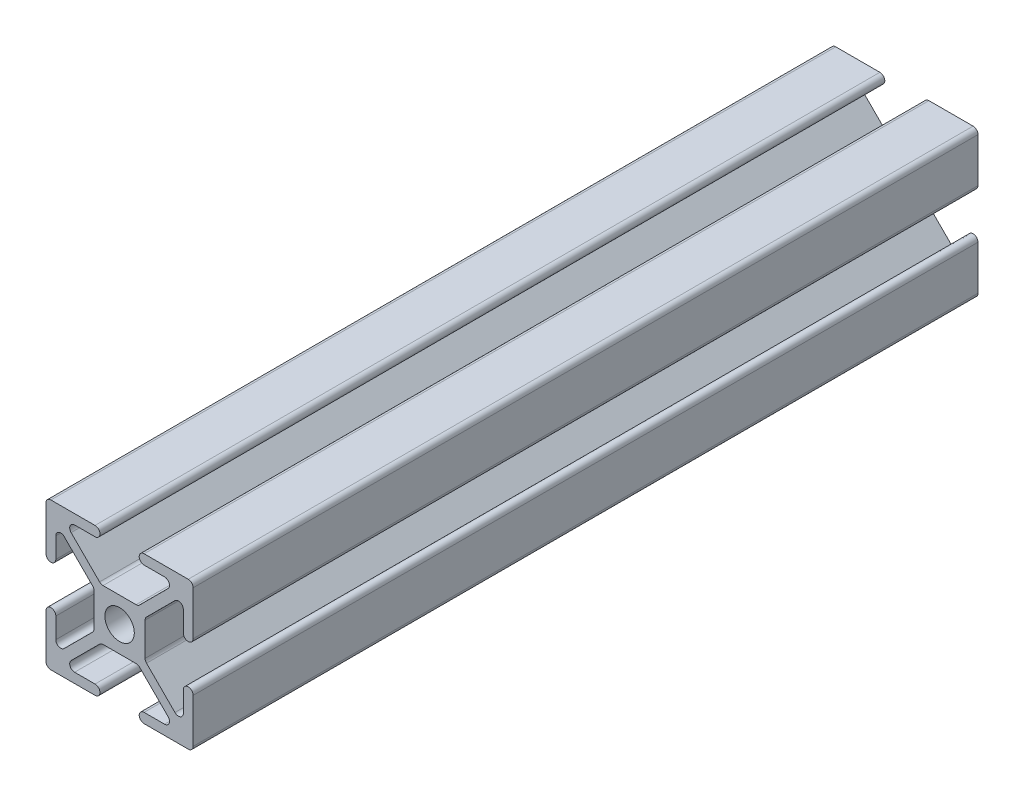
SolidWorks part; units mm, degrees
ref_plane "Alzado" through (0, 0, 0) normal (0, 0, 1) x (1, 0, 0)
ref_plane "Planta" through (0, 0, 0) normal (0, 1, 0) x (1, 0, 0)
ref_plane "Vista lateral" through (0, 0, 0) normal (1, 0, 0) x (0, 0, -1)
sketch "Croquis1" plane through (0, 0, 0) normal (0, 0, 1) x (1, 0, 0)
  line L1 (-14, 15) -> (14, 15)
  line L2 (-15, 14) -> (-15, -14)
  line L3 (-14, -15) -> (14, -15)
  line L4 (15, 14) -> (15, -14)
  line L5 (-15, 15) -> (15, -15) construction
  line L6 (-15, -15) -> (15, 15) construction
  arc A0 (-14, 15) -> (-15, 14) centre (-14, 14) ccw
  arc A1 (14, -15) -> (15, -14) centre (14, -14) ccw
  arc A2 (-14, -15) -> (-15, -14) centre (-14, -14) cw
  arc A3 (15, 14) -> (14, 15) centre (14, 14) ccw
  point P0 (0, 0)
  dimension "D3" = 1
  dimension "D4" = 1
  dimension "D1" = 30
  dimension "D2" = 30
extrude "Saliente-Extruir1" add sketch "Croquis1" against normal blind 190
sketch "Croquis2" plane through (0, 0, 0) normal (0, 0, 1) x (1, 0, 0)
  circle A0 centre (0, 0) radius 3
  dimension "D1" = 6
sketch "Croquis3" plane through (0, 0, 0) normal (0, 0, 1) x (1, 0, 0)
  line L0 (-15, 0) -> (15, 0) construction
  line L1 (4.0787, -5.4929) -> (9.8787, -11.2929)
  line L2 (-11.2929, 9.8787) -> (-5.4929, 4.0787)
  line L3 (-9.8787, 11.2929) -> (-4.0787, 5.4929)
  line L4 (-13, 9.1716) -> (-13, 5)
  line L5 (-15, 14) -> (-15, -14) construction
  line L6 (-5.2, 3.3716) -> (-5.2, -3.3716)
  line L7 (-9.1716, 13) -> (-5, 13)
  line L8 (9.8787, 11.2929) -> (4.0787, 5.4929)
  line L9 (11.2929, 9.8787) -> (5.4929, 4.0787)
  line L10 (-3.3716, 5.2) -> (3.3716, 5.2)
  line L11 (14, 15) -> (-14, 15) construction
  line L12 (13, 9.1716) -> (13, 5)
  line L13 (5.2, 3.3716) -> (5.2, -3.3716)
  line L14 (15, -14) -> (15, 14) construction
  line L15 (-9.1716, -13) -> (-5, -13)
  line L16 (-3.3716, -5.2) -> (3.3716, -5.2)
  line L17 (-14, -15) -> (14, -15) construction
  line L18 (-5.4929, -4.0787) -> (-11.2929, -9.8787)
  line L19 (5.4929, -4.0787) -> (11.2929, -9.8787)
  line L20 (-4.0787, -5.4929) -> (-9.8787, -11.2929)
  line L21 (5, -13) -> (9.1716, -13)
  line L22 (-13, -5) -> (-13, -9.1716)
  line L23 (13, -5) -> (13, -9.1716)
  line L24 (0, 15) -> (0, -5.2) construction
  line L34 (5, 13) -> (9.1716, 13)
  arc A0 (9.8787, 11.2929) -> (9.1716, 13) centre (9.1716, 12) ccw
  arc A1 (-9.8787, 11.2929) -> (-9.1716, 13) centre (-9.1716, 12) cw
  arc A2 (9.8787, 11.2929) -> (9.1716, 13) centre (9.1716, 12) ccw
  arc A3 (13, 9.1716) -> (11.2929, 9.8787) centre (12, 9.1716) ccw
  arc A4 (11.2929, -9.8787) -> (13, -9.1716) centre (12, -9.1716) ccw
  arc A5 (9.1716, -13) -> (9.8787, -11.2929) centre (9.1716, -12) ccw
  arc A6 (-9.1716, -13) -> (-9.8787, -11.2929) centre (-9.1716, -12) cw
  arc A7 (-11.2929, -9.8787) -> (-13, -9.1716) centre (-12, -9.1716) cw
  arc A8 (-13, 9.1716) -> (-11.2929, 9.8787) centre (-12, 9.1716) cw
  arc A9 (-4.0787, -5.4929) -> (-3.3716, -5.2) centre (-3.3716, -6.2) cw
  arc A10 (3.3716, -5.2) -> (4.0787, -5.4929) centre (3.3716, -6.2) cw
  arc A11 (5.4929, -4.0787) -> (5.2, -3.3716) centre (6.2, -3.3716) cw
  arc A12 (5.2, 3.3716) -> (5.4929, 4.0787) centre (6.2, 3.3716) cw
  arc A13 (3.3716, 5.2) -> (4.0787, 5.4929) centre (3.3716, 6.2) ccw
  arc A14 (-3.3716, 5.2) -> (-4.0787, 5.4929) centre (-3.3716, 6.2) cw
  arc A15 (-5.4929, -4.0787) -> (-5.2, -3.3716) centre (-6.2, -3.3716) ccw
  arc A16 (-5.2, 3.3716) -> (-5.4929, 4.0787) centre (-6.2, 3.3716) ccw
  circle A17 centre (-14, -5) radius 1
  circle A18 centre (-14, 5) radius 1
  circle A19 centre (-5, -14) radius 1
  circle A20 centre (5, -14) radius 1
  circle A21 centre (14, 5) radius 1
  circle A22 centre (14, -5) radius 1
  circle A23 centre (-5, 14) radius 1
  circle A24 centre (5, 14) radius 1
  point P20 (-11.5858, -13)
  point P30 (-13, -11.5858)
  point P43 (-3.7858, -5.2)
  point P50 (3.7858, -5.2)
  point P53 (5.2, -3.7858)
  point P62 (-5.2, -3.7858)
  line M2 (-15, 14) -> (-15, -14)
  line M4 (-14, -15) -> (14, -15)
  line M6 (15, -14) -> (15, 14)
  line M8 (14, 15) -> (-14, 15)
  dimension "D6" = 9.8
  dimension "D7" = 2
  dimension "D12" = 2
  dimension "D19" = 1
  dimension "D2" = 1
  dimension "D3" = 1
  dimension "D4" = 1
  dimension "D16" = 1
  dimension "D5" = 2
  dimension "D8" = 9.8
  dimension "D9" = 2
  dimension "D10" = 9.8
  dimension "D11" = 9.8
  dimension "D15" = 1
  dimension "D20" = 1
  dimension "D23" = 1
  dimension "D24" = 1
  dimension "D27" = 1
  dimension "D28" = 1
extrude "Cortar-Extruir1" cut sketch "Croquis2" against normal through all
extrude "Cortar-Extruir3" cut sketch "Croquis3" against normal through all contours A18 A17 L22 A7 L18 A15 L6 A16 L2 A8 L4 M2 | A24 A23 L7 A1 L3 A14 L10 A13 L8 A0 L34 M8 | A20 L21 A5 L1 A10 L16 A9 L20 A6 L15 A19 M4 | A22 A21 L12 A3 L9 A12 L13 A11 L19 A4 L23 M6
sketch "Croquis4" plane through (0, 15, 0) normal (0, 1, 0) x (1, 0, 0)
  line L1 (15, 0) -> (-18.1276, 0)
  line L2 (15, 0) -> (15, 30)
  line L3 (15, 30) -> (-18.1276, 30)
  line L4 (-18.1276, 0) -> (-18.1276, 30)
extrude "Cortar-Extruir4" cut sketch "Croquis4" against normal blind 38
